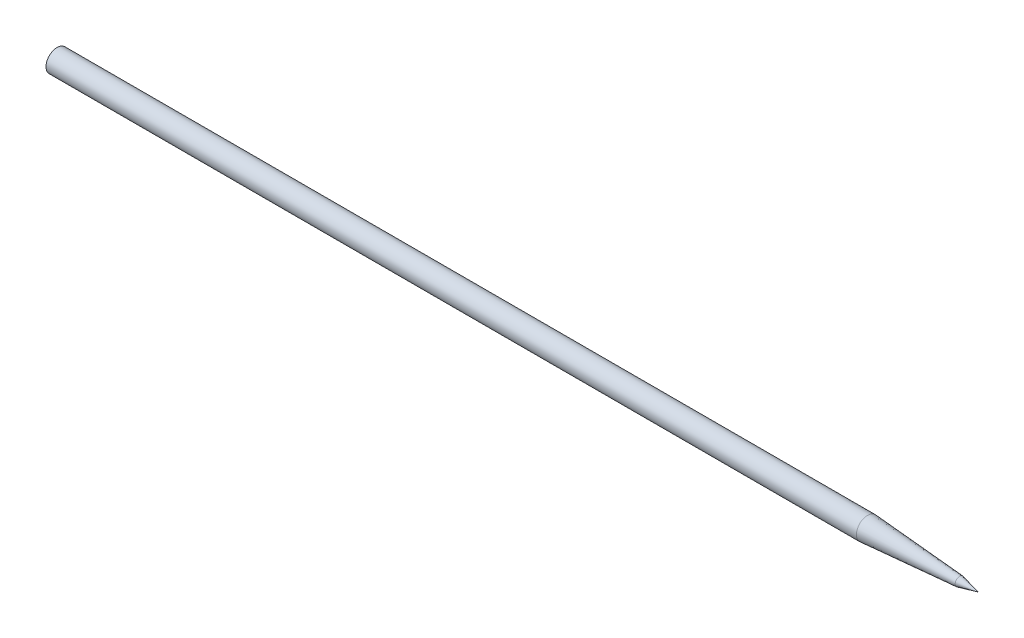
SolidWorks part; units mm, degrees
ref_plane "Front Plane" through (0, 0, 0) normal (0, 0, 1) x (1, 0, 0)
ref_plane "Top Plane" through (0, 0, 0) normal (0, 1, 0) x (1, 0, 0)
ref_plane "Right Plane" through (0, 0, 0) normal (1, 0, 0) x (0, 0, -1)
sketch "Sketch1" plane through (0, 0, 0) normal (0, 0, 1) x (1, 0, 0)
  line L0 (0, 0) -> (0, 3)
  line L1 (0, 3) -> (220, 3)
  line L2 (220, 3) -> (245, 1.2)
  line L3 (245, 1.2) -> (250, 0)
  line L4 (250, 0) -> (0, 0)
  line L5 (-10, 0) -> (1000, 0) construction
revolve "Revolve1" add sketch "Sketch1" angle 360 about L5
